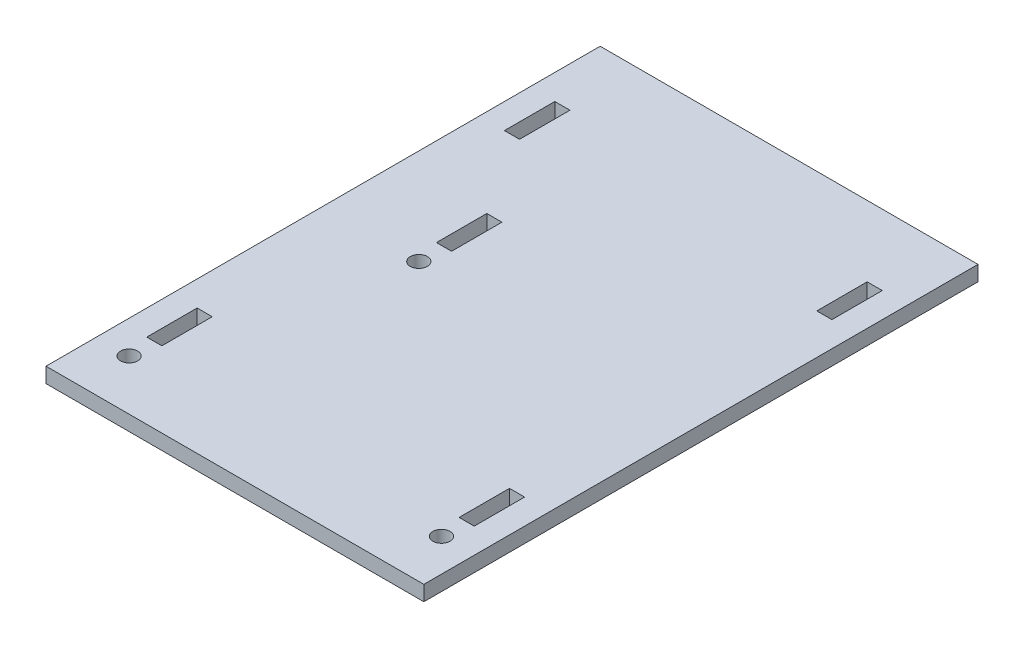
SolidWorks part; units mm, degrees
ref_plane "Front Plane" through (0, 0, 0) normal (0, 0, 1) x (1, 0, 0)
ref_plane "Top Plane" through (0, 0, 0) normal (0, 1, 0) x (1, 0, 0)
ref_plane "Right Plane" through (0, 0, 0) normal (1, 0, 0) x (0, 0, -1)
sketch "Sketch1" plane through (0, 0, 0) normal (0, 1, 0) x (1, 0, 0)
  line L1 (0, 0) -> (75, 0)
  line L2 (0, 0) -> (0, 110)
  line L3 (0, 110) -> (75, 110)
  line L4 (75, 0) -> (75, 110)
  dimension "D1" = 75
  dimension "D2" = 110
extrude "Boss-Extrude1" add sketch "Sketch1" along normal blind 3
sketch "Sketch2" plane through (0, 3, 0) normal (0, 1, 0) x (1, 0, 0)
  line L1 (5, 96) -> (8, 96)
  line L2 (5, 96) -> (5, 86)
  line L3 (5, 86) -> (8, 86)
  line L4 (8, 96) -> (8, 86)
  line L9 (67, 96) -> (70, 96)
  line L10 (67, 96) -> (67, 86)
  line L11 (67, 86) -> (70, 86)
  line L12 (70, 96) -> (70, 86)
  line L13 (67, 25) -> (70, 25)
  line L14 (67, 25) -> (67, 15)
  line L15 (67, 15) -> (70, 15)
  line L16 (70, 25) -> (70, 15)
  line L17 (5, 25) -> (8, 25)
  line L18 (5, 25) -> (5, 15)
  line L19 (5, 15) -> (8, 15)
  line L20 (8, 25) -> (8, 15)
  line L25 (20.5, 60) -> (17.5, 60)
  line L26 (20.5, 60) -> (20.5, 70)
  line L27 (20.5, 70) -> (17.5, 70)
  line L28 (17.5, 60) -> (17.5, 70)
extrude "Cut-Extrude1" cut sketch "Sketch2" against normal blind 3
hole_wizard "M3 Clearance Hole1" positions "Sketch3" profile "Sketch4" hole size "M3" standard "ANSI Metric"
sketch "Sketch3" plane through (0, 3, 0) normal (0, 1, 0) x (1, 0, 0)
  line L0 (75, 0) -> (75, 110) construction
  line L1 (0, 110) -> (0, 0) construction
  line L2 (0, 0) -> (75, 0) construction
  line L3 (75, 110) -> (0, 110) construction
  point P0 (6.5, 10)
  point P2 (68.5, 10)
  point P11 (19, 55)
  dimension "D1" = 6.5
  dimension "D2" = 6.5
  dimension "D3" = 10
  dimension "D4" = 10
  dimension "D5" = 19
  dimension "D6" = 55
sketch "Sketch4" plane through (6.5, 3, -10) normal (1, 0, 0) x (0, 0, 1)
  line L0 (0, 0) -> (0, 4.0215)
  line L1 (0, 4.0215) -> (1.7, 3)
  line L2 (1.7, 3) -> (1.7, 0)
  line L5 (1.7, 0) -> (0, 0)
  line L10 (0, 4.0215) -> (-1.7, 3) construction
  line L11 (0, -6.35) -> (0, 107.95) construction
  dimension "Hole Dia." = 3.4
  dimension "Hole Depth" = 3
  dimension "Drill Angle" = 118
